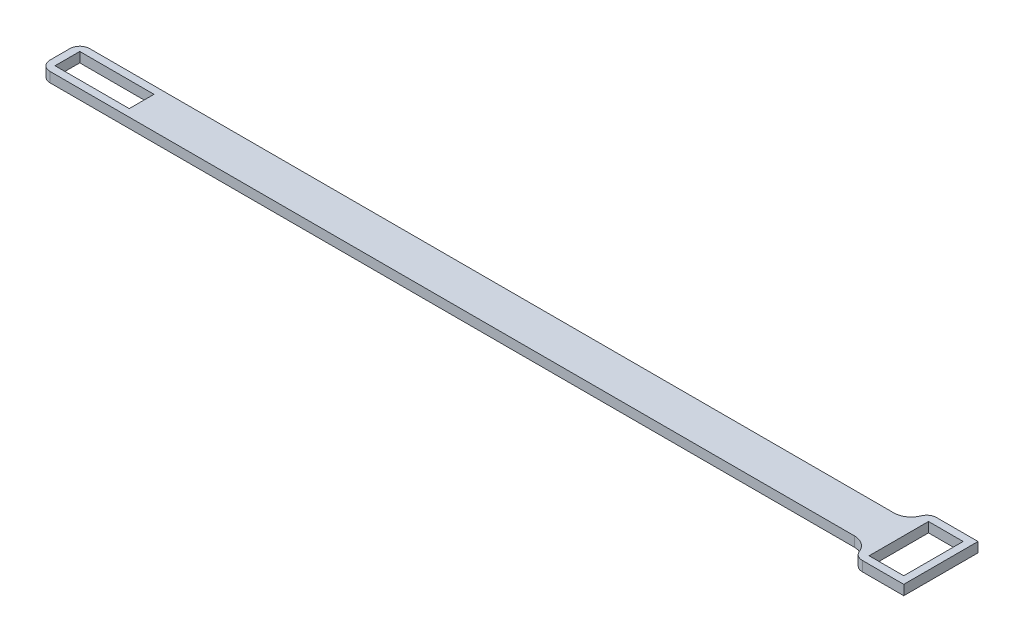
SolidWorks part; units mm, degrees
ref_plane "Front Plane" through (0, 0, 0) normal (0, 0, 1) x (1, 0, 0)
ref_plane "Top Plane" through (0, 0, 0) normal (0, 1, 0) x (1, 0, 0)
ref_plane "Right Plane" through (0, 0, 0) normal (1, 0, 0) x (0, 0, -1)
sketch "Sketch1" plane through (0, 0, 0) normal (0, 1, 0) x (1, 0, 0)
  line L0 (-1000, 0) -> (49000, 0) construction
  line L1 (-75, 4) -> (75, 4)
  line L2 (-75, 4) -> (-75, -4)
  line L3 (-75, -4) -> (75, -4)
  line L4 (75, 4) -> (75, -4)
  line L5 (-76.5, 2.5) -> (-91.5, 2.5)
  line L6 (-76.5, 2.5) -> (-76.5, -2.5)
  line L7 (-76.5, -2.5) -> (-91.5, -2.5)
  line L8 (-91.5, 2.5) -> (-91.5, -2.5)
  line L9 (76.5, 6) -> (83.5, 6)
  line L10 (76.5, 6) -> (76.5, -6)
  line L11 (76.5, -6) -> (83.5, -6)
  line L12 (83.5, 6) -> (83.5, -6)
  line L13 (0, 0) -> (0, 14.2615) construction
  line L14 (-93, 4) -> (-75, 4)
  line L15 (-93, 4) -> (-93, -4)
  line L16 (-93, -4) -> (-75, -4)
  line L17 (-75, 4) -> (-75, -4)
  line L18 (75, 7.5) -> (85, 7.5)
  line L19 (75, 7.5) -> (75, -7.5)
  line L20 (75, -7.5) -> (85, -7.5)
  line L21 (85, 7.5) -> (85, -7.5)
  circle A4 centre (71.5, 7.5) radius 3.5
  circle A5 centre (71.5, -7.5) radius 3.5
  point P13 (-75, 0)
  point P24 (-91.5, 0)
  point P25 (-84, 4)
  point P26 (-84, -4)
  point P27 (75, 0)
  point P28 (75, 0)
  point P29 (-75, 0)
  point P35 (0, 4)
  dimension "D1" = 150
  dimension "D2" = 15
  dimension "D3" = 5
  dimension "D4" = 8
  dimension "D5" = 12
  dimension "D6" = 7
  dimension "D7" = 1.5
  dimension "D8" = 1.5
  dimension "D9" = 1.5
  dimension "D10" = 1.5
  dimension "D11" = 1.5
  dimension "D12" = 1.5
  dimension "D13" = 1.5
  dimension "D14" = 1.5
extrude "Boss-Extrude1" add sketch "Sketch1" along normal blind 2
fillet "Fillet1" radius 2 4 edges at (-93, 1, 4) (-93, 1, -4) (75, 1, 7.5) (75, 1, -7.5)
